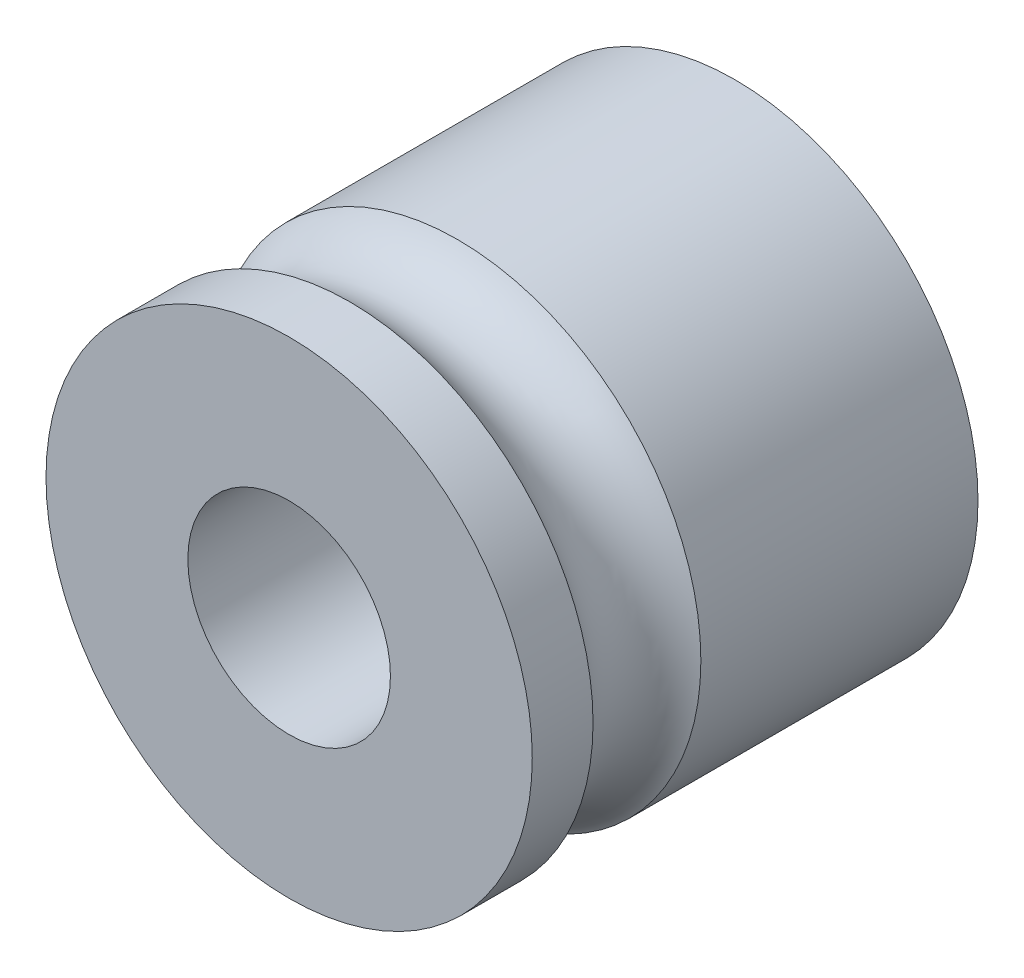
SolidWorks part; units mm, degrees
material "1.2085 (X33CrS16)"
ref_plane "Přední rovina" through (0, 0, 0) normal (0, 0, 1) x (1, 0, 0)
ref_plane "Horní rovina" through (0, 0, 0) normal (0, 1, 0) x (1, 0, 0)
ref_plane "Pravá rovina" through (0, 0, 0) normal (1, 0, 0) x (0, 0, -1)
sketch "Skica1" plane through (0, 0, 0) normal (0, 0, 1) x (1, 0, 0)
  circle A0 centre (0, 0) radius 6
  circle A1 centre (0, 0) radius 2.5
  dimension "D1" = 12
  dimension "D2" = 5
extrude "Přidat vysunutím1" add sketch "Skica1" along normal blind 11
sketch "Skica2" plane through (0, 0, 0) normal (1, 0, 0) x (0, 0, -1)
  line L0 (0, 6) -> (-11, 6) construction
  line L1 (0, 0) -> (-20.5827, 0) construction
  line L2 (-6.8389, 6) -> (-9.5, 6)
  arc A0 (-9.5, 6) -> (-6.8389, 6) centre (-8.1695, 6.8052) ccw
  point P3 (-8.1695, 5.25)
  dimension "D1" = 1.5
  dimension "D2" = 0.75
revolve "Odebrat rotací1" cut sketch "Skica2" angle 360 about L1
sketch "Skica3" plane through (0, 0, 0) normal (1, 0, 0) x (0, 0, -1)
  circle A0 centre (-2.7099, 0) radius 1.5
  dimension "D1" = 3
extrude "Odebrat vysunutím1" cut sketch "Skica3" against normal blind 11
